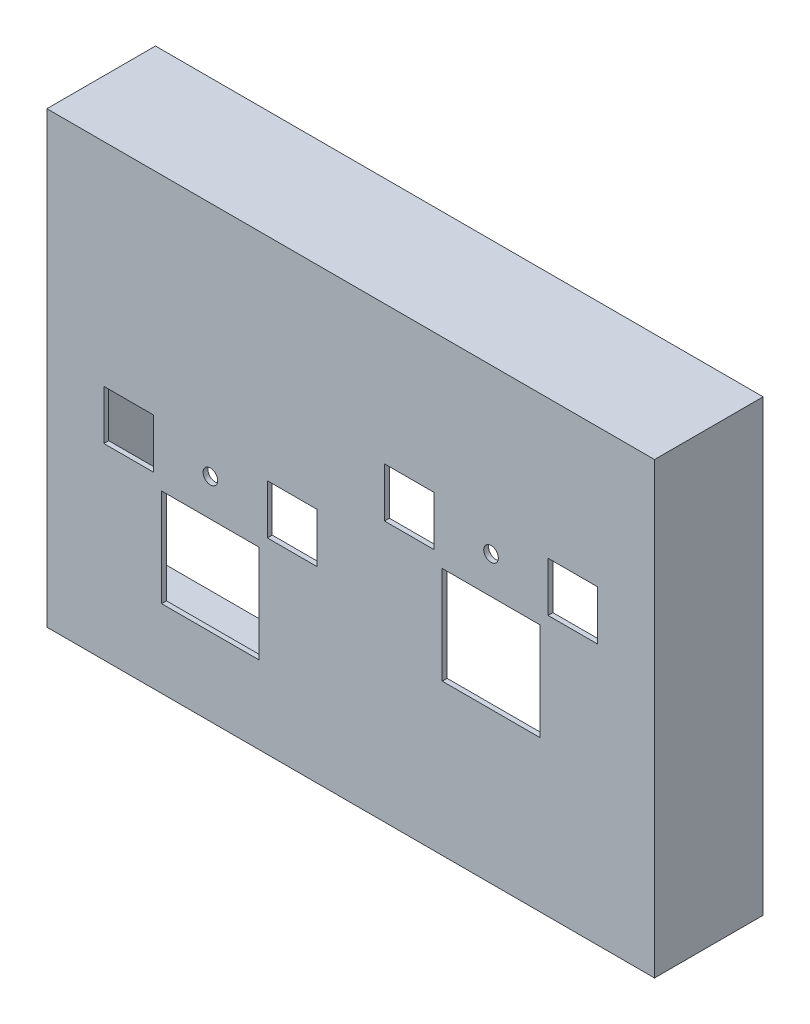
SolidWorks part; units mm, degrees
material "6061-T6 (SS)"
ref_plane "Front" through (0, 0, 0) normal (0, 0, 1) x (1, 0, 0)
ref_plane "Top" through (0, 0, 0) normal (0, 1, 0) x (1, 0, 0)
ref_plane "Right" through (0, 0, 0) normal (1, 0, 0) x (0, 0, -1)
sketch "Croquis1" plane through (0, 0, 0) normal (0, 0, 1) x (1, 0, 0)
  line L1 (0, 0) -> (249, 0)
  line L2 (0, 0) -> (0, 84)
  line L3 (0, 84) -> (249, 84)
  line L4 (249, 0) -> (249, 84)
  dimension "D1" = 249
  dimension "84" = 84
extrude "Saliente-Extruir1" add sketch "Croquis1" along normal blind 44.5
shell "Vaciado1" thickness 2
sketch "Croquis2" plane through (0, 0, 42.5) normal (0, 0, -1) x (-1, 0, 0)
  line L0 (-249, 84) -> (0, 84) construction
  line L1 (-110.65, 37.15) -> (-90.35, 37.15)
  line L2 (-110.65, 37.15) -> (-110.65, 16.85)
  line L3 (-110.65, 16.85) -> (-90.35, 16.85)
  line L4 (-90.35, 37.15) -> (-90.35, 16.85)
  line L6 (-43.65, 37.15) -> (-23.35, 37.15)
  line L7 (-43.65, 37.15) -> (-43.65, 16.85)
  line L8 (-43.65, 16.85) -> (-23.35, 16.85)
  line L9 (-23.35, 37.15) -> (-23.35, 16.85)
  line L11 (-225.65, 67.15) -> (-205.35, 67.15)
  line L12 (-225.65, 67.15) -> (-225.65, 46.85)
  line L13 (-225.65, 46.85) -> (-205.35, 46.85)
  line L14 (-205.35, 67.15) -> (-205.35, 46.85)
  line L15 (-158.65, 67.15) -> (-138.35, 67.15)
  line L16 (-158.65, 67.15) -> (-158.65, 46.85)
  line L17 (-158.65, 46.85) -> (-138.35, 46.85)
  line L18 (-138.35, 67.15) -> (-138.35, 46.85)
  line L19 (0, 84) -> (0, 0) construction
  line L20 (-249, 0) -> (-249, 84) construction
  point P22 (-148.5, 46.85)
  dimension "D1" = 20.3
  dimension "D2" = 23.35
  dimension "D3" = 9.7
  dimension "46." = 46.7
  dimension "D4" = 16.85
  dimension "D5" = 46.7
  dimension "D6" = 23.35
extrude "Cortar-Extruir1" cut sketch "Croquis2" against normal blind 45
sketch "Croquis3" plane through (0, 0, 0) normal (0, 0, -1) x (-1, 0, 0)
  line L0 (-2, 82) -> (-2, 2) construction
  line L1 (-247, 82) -> (-2, 82)
  line L2 (-247, 82) -> (-247, 72)
  line L3 (-247, 72) -> (-2, 72)
  line L4 (-2, 82) -> (-2, 72)
  line L5 (-247, 2) -> (-247, 82) construction
  line L6 (-2, 2) -> (-247, 2)
  line L7 (-2, 2) -> (-2, 12)
  line L8 (-2, 12) -> (-247, 12)
  line L9 (-247, 2) -> (-247, 12)
  dimension "D1" = 10
extrude "Saliente-Extruir2" [suppressed] add sketch "Croquis3" against normal blind 2
sketch "Croquis4" plane through (0, 0, 44.5) normal (0, 0, 1) x (1, 0, 0)
  line L0 (33.5, 37.15) -> (33.5, 16.85) construction
  line L1 (23.35, 37.15) -> (43.65, 37.15) construction
  line L2 (43.65, 16.85) -> (23.35, 16.85) construction
  line L3 (33.5, 27) -> (67, 27) construction
  line L4 (138.35, 57) -> (158.65, 57) construction
  line L5 (138.35, 46.85) -> (138.35, 67.15) construction
  line L6 (158.65, 67.15) -> (158.65, 46.85) construction
  circle A0 centre (67, 27) radius 3
  circle A1 centre (182, 57) radius 3
  point P18 (148.5, 57)
  dimension "D1" = 33.5
  dimension "D2" = 6
  dimension "D3" = 33.5
extrude "Cortar-Extruir2" cut sketch "Croquis4" against normal blind 10
sketch "Croquis5" plane through (0, 0, 44.5) normal (0, 0, 1) x (1, 0, 0)
  line L0 (249, 0) -> (249, 84) construction
  line L1 (0, 84) -> (249, 84)
  line L2 (0, 84) -> (0, 124)
  line L3 (0, 124) -> (249, 124)
  line L4 (249, 84) -> (249, 124)
  line L6 (0, 0) -> (249, 0)
  line L7 (0, 0) -> (0, -60)
  line L8 (0, -60) -> (249, -60)
  line L9 (249, 0) -> (249, -60)
  dimension "D1" = 40
  dimension "D2" = 60
extrude "Saliente-Extruir3" add sketch "Croquis5" against normal up to surface (44.5 mm away) up to face at (124.5, 42, 0)
ref_plane "Plano1" through (0, -58, 0) normal (0, -1, 0) x (-1, 0, 0)
sketch "Croquis7" plane through (0, -58, 0) normal (0, -1, 0) x (-1, 0, 0)
  line L8 (-2, -42.5) -> (-2, -2)
  line L9 (-2, -2) -> (-247, -2)
  line L10 (-247, -2) -> (-247, -42.5)
  line L11 (-247, -42.5) -> (-2, -42.5)
  line L12 (-2, -42.5) -> (-2, -2)
  line L13 (-2, -2) -> (-247, -2)
  line L14 (-247, -2) -> (-247, -42.5)
  line L15 (-247, -42.5) -> (-2, -42.5)
  dimension "D1" = 2
extrude "Cortar-Extruir3" cut sketch "Croquis7" against normal offset from surface (180 mm away) 2 up to face at (124.5, 124, 22.25)
sketch "Croquis8" plane through (0, 0, 0) normal (0, 0, -1) x (-1, 0, 0)
  line L8 (-2, -58) -> (-2, 122)
  line L9 (-2, 122) -> (-247, 122)
  line L10 (-247, 122) -> (-247, -58)
  line L11 (-247, -58) -> (-2, -58)
  line L12 (-2, -58) -> (-2, 122)
  line L13 (-2, 122) -> (-247, 122)
  line L14 (-247, 122) -> (-247, -58)
  line L15 (-247, -58) -> (-2, -58)
  dimension "D1" = 2
extrude "Cortar-Extruir4" cut sketch "Croquis8" against normal offset from surface (42.5 mm away) 2 up to face at (70, 27, 44.5)
sketch "Croquis9" plane through (0, 0, 44.5) normal (0, 0, 1) x (1, 0, 0)
  line L0 (110.65, 16.85) -> (90.35, 16.85) construction
  line L1 (47, 11.85) -> (87, 11.85)
  line L2 (47, 11.85) -> (47, -28.15)
  line L3 (47, -28.15) -> (87, -28.15)
  line L4 (87, 11.85) -> (87, -28.15)
  line L5 (162, 41.85) -> (202, 41.85)
  line L6 (162, 41.85) -> (162, 1.85)
  line L7 (162, 1.85) -> (202, 1.85)
  line L8 (202, 41.85) -> (202, 1.85)
  line L9 (43.65, 37.15) -> (43.65, 16.85) construction
  line L10 (158.65, 46.85) -> (138.35, 46.85) construction
  line L11 (158.65, 67.15) -> (158.65, 46.85) construction
  dimension "D1" = 5
  dimension "D2" = 3.35
  dimension "D3" = 40
  dimension "D4" = 5
  dimension "D5" = 3.35
extrude "Cortar-Extruir5" cut sketch "Croquis9" against normal blind 2
